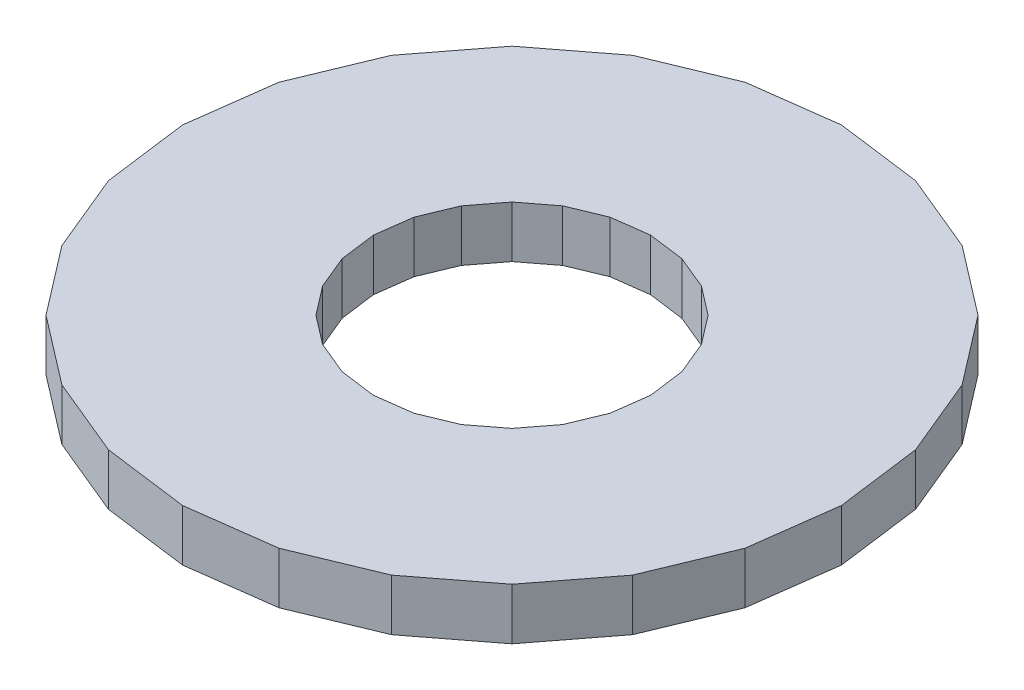
SolidWorks part; units mm, degrees
ref_plane "Front Plane" through (0, 0, 0) normal (0, 0, 1) x (1, 0, 0)
ref_plane "Top Plane" through (0, 0, 0) normal (0, 1, 0) x (1, 0, 0)
ref_plane "Right Plane" through (0, 0, 0) normal (1, 0, 0) x (0, 0, -1)
sketch "Sketch2" plane through (0, 0, 0) normal (0, 1, 0) x (1, 0, 0)
  line L0 (0, 0) -> (-51.1704, 0) construction
  line L1 (-121.6231, 0) -> (-117.4789, -31.4784)
  line L2 (-117.4789, -31.4784) -> (-105.3287, -60.8115)
  line L3 (-105.3287, -60.8115) -> (-86.0005, -86.0005)
  line L4 (-86.0005, -86.0005) -> (-60.8115, -105.3287)
  line L5 (-60.8115, -105.3287) -> (-31.4784, -117.4789)
  line L6 (-31.4784, -117.4789) -> (0, -121.6231)
  line L7 (0, -121.6231) -> (31.4784, -117.4789)
  line L8 (31.4784, -117.4789) -> (60.8115, -105.3287)
  line L9 (60.8115, -105.3287) -> (86.0005, -86.0005)
  line L10 (86.0005, -86.0005) -> (105.3287, -60.8115)
  line L11 (105.3287, -60.8115) -> (117.4789, -31.4784)
  line L12 (117.4789, -31.4784) -> (121.6231, 0)
  line L13 (121.6231, 0) -> (117.4789, 31.4784)
  line L14 (117.4789, 31.4784) -> (105.3287, 60.8115)
  line L15 (105.3287, 60.8115) -> (86.0005, 86.0005)
  line L16 (86.0005, 86.0005) -> (60.8115, 105.3287)
  line L17 (60.8115, 105.3287) -> (31.4784, 117.4789)
  line L18 (31.4784, 117.4789) -> (0, 121.6231)
  line L19 (0, 121.6231) -> (-31.4784, 117.4789)
  line L20 (-31.4784, 117.4789) -> (-60.8115, 105.3287)
  line L21 (-60.8115, 105.3287) -> (-86.0005, 86.0005)
  line L22 (-86.0005, 86.0005) -> (-105.3287, 60.8115)
  line L23 (-105.3287, 60.8115) -> (-117.4789, 31.4784)
  line L24 (-117.4789, 31.4784) -> (-121.6231, 0)
  line L25 (-51.1704, 0) -> (-49.4268, -13.2439)
  line L26 (-49.4268, -13.2439) -> (-44.3148, -25.5852)
  line L27 (-44.3148, -25.5852) -> (-36.1829, -36.1829)
  line L28 (-36.1829, -36.1829) -> (-25.5852, -44.3148)
  line L29 (-25.5852, -44.3148) -> (-13.2439, -49.4268)
  line L30 (-13.2439, -49.4268) -> (0, -51.1704)
  line L31 (0, -51.1704) -> (13.2439, -49.4268)
  line L32 (13.2439, -49.4268) -> (25.5852, -44.3148)
  line L33 (25.5852, -44.3148) -> (36.1829, -36.1829)
  line L34 (36.1829, -36.1829) -> (44.3148, -25.5852)
  line L35 (44.3148, -25.5852) -> (49.4268, -13.2439)
  line L36 (49.4268, -13.2439) -> (51.1704, 0)
  line L37 (51.1704, 0) -> (49.4268, 13.2439)
  line L38 (49.4268, 13.2439) -> (44.3148, 25.5852)
  line L39 (44.3148, 25.5852) -> (36.1829, 36.1829)
  line L40 (36.1829, 36.1829) -> (25.5852, 44.3148)
  line L41 (25.5852, 44.3148) -> (13.2439, 49.4268)
  line L42 (13.2439, 49.4268) -> (0, 51.1704)
  line L43 (0, 51.1704) -> (-13.2439, 49.4268)
  line L44 (-13.2439, 49.4268) -> (-25.5852, 44.3148)
  line L45 (-25.5852, 44.3148) -> (-36.1829, 36.1829)
  line L46 (-36.1829, 36.1829) -> (-44.3148, 25.5852)
  line L47 (-44.3148, 25.5852) -> (-49.4268, 13.2439)
  line L48 (-49.4268, 13.2439) -> (-51.1704, 0)
  line L49 (-121.6231, 0) -> (-51.1704, 0) construction
  circle A0 centre (0, 0) radius 120.5826 construction
  circle A1 centre (0, 0) radius 50.7326 construction
  dimension "D1" = 31.75
  dimension "D2" = 69.85
extrude "Boss-Extrude2" add sketch "Sketch2" along normal blind 19.05
